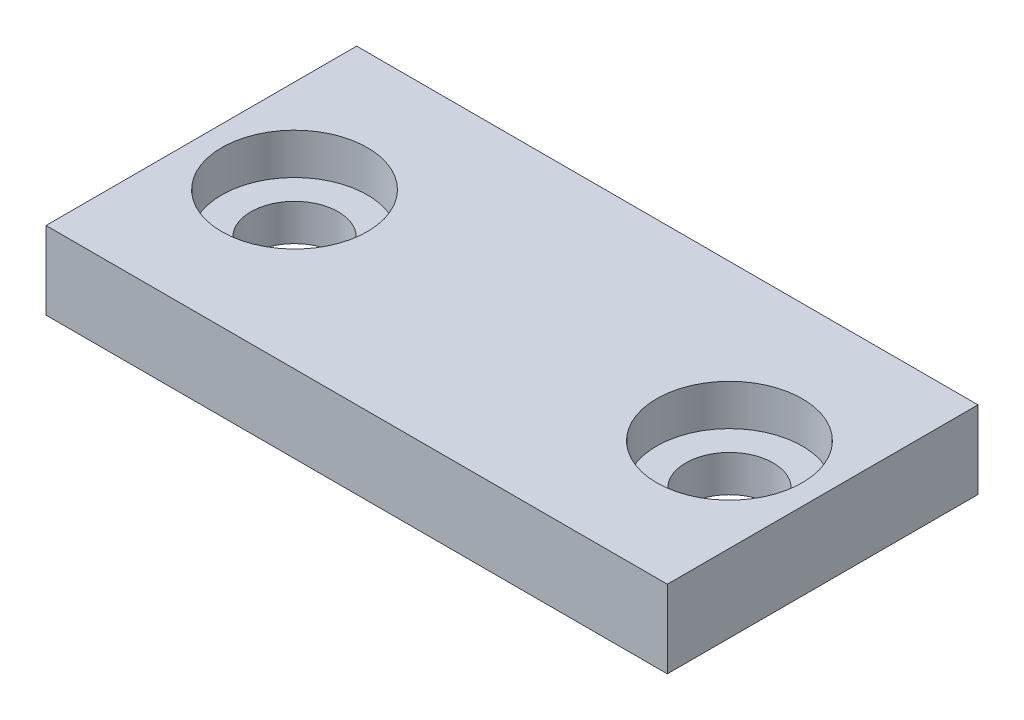
SolidWorks part; units mm, degrees
ref_plane "Front Plane" through (0, 0, 0) normal (0, 0, 1) x (1, 0, 0)
ref_plane "Top Plane" through (0, 0, 0) normal (0, 1, 0) x (1, 0, 0)
ref_plane "Right Plane" through (0, 0, 0) normal (1, 0, 0) x (0, 0, -1)
sketch "Sketch1" plane through (0, 0, 0) normal (0, 1, 0) x (1, 0, 0)
  line L1 (0, 0) -> (50.8, 0)
  line L2 (0, 0) -> (0, 25.4)
  line L3 (0, 25.4) -> (50.8, 25.4)
  line L4 (50.8, 0) -> (50.8, 25.4)
  dimension "D1" = 50.8
  dimension "D2" = 25.4
extrude "Boss-Extrude1" add sketch "Sketch1" along normal blind 6.35
hole_wizard "CBORE for 1/4 Button Head Cap Screw1" positions "Sketch3" profile "Sketch2" counterbore size "1/4" standard "ANSI Inch" end condition through all
sketch "Sketch3" plane through (0, 6.35, 0) normal (0, 1, 0) x (1, 0, 0)
  line L0 (50.8, 25.4) -> (0, 25.4) construction
  line L1 (50.8, 0) -> (50.8, 25.4) construction
  line L2 (0, 25.4) -> (0, 0) construction
  point P0 (7.62, 12.7)
  point P2 (43.18, 12.7)
  point P13 (50.8, 12.7)
  dimension "D1" = 12.7
  dimension "D2" = 12.7
  dimension "D3" = 7.62
  dimension "D4" = 7.62
sketch "Sketch2" plane through (7.62, 6.35, -12.7) normal (1, 0, 0) x (0, 0, 1)
  line L0 (0, 0) -> (0, 6.35)
  line L1 (0, 6.35) -> (3.5712, 6.35)
  line L3 (3.5712, 6.35) -> (3.5712, 3.3528)
  line L4 (3.5712, 3.3528) -> (5.9538, 3.3528)
  line L5 (5.9538, 3.3528) -> (5.9538, 0)
  line L7 (5.9538, 0) -> (0, 0)
  line L11 (0, -6.35) -> (0, 107.95) construction
  dimension "Thru Hole Dia." = 7.1425
  dimension "Thru Hole Depth" = 6.35
  dimension "C'Bore Dia." = 11.9075
  dimension "C'Bore Depth" = 3.3528
